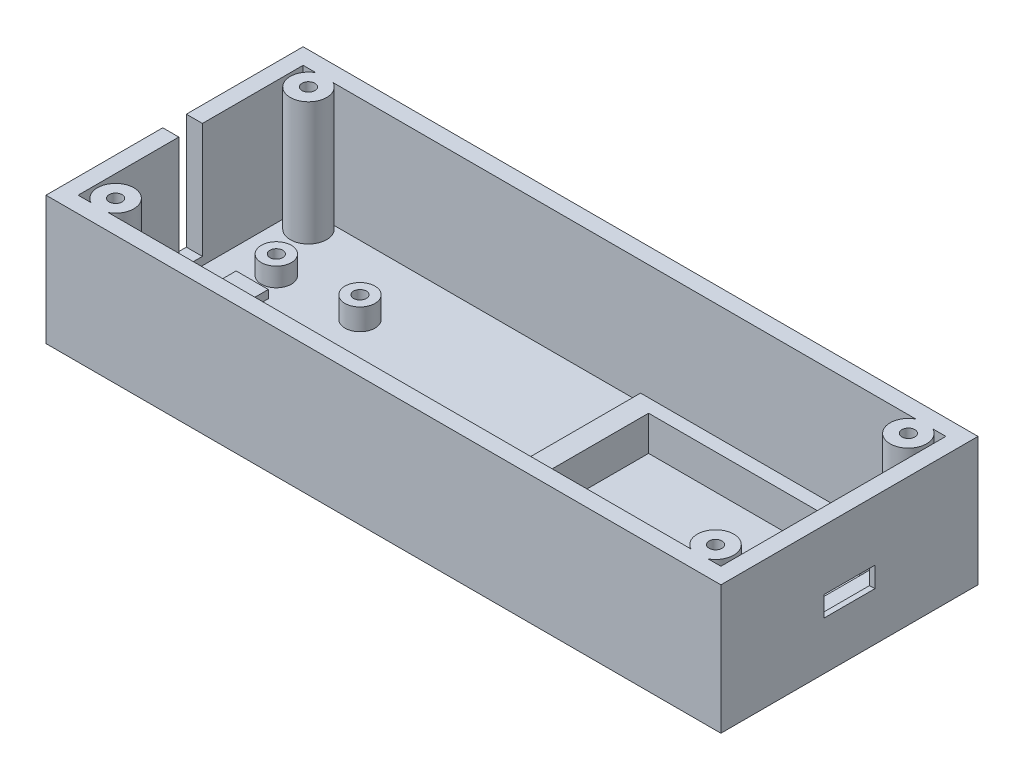
SolidWorks part; units mm, degrees
ref_plane "Front Plane" through (0, 0, 0) normal (0, 0, 1) x (1, 0, 0)
ref_plane "Top Plane" through (0, 0, 0) normal (0, 1, 0) x (1, 0, 0)
ref_plane "Right Plane" through (0, 0, 0) normal (1, 0, 0) x (0, 0, -1)
sketch "Sketch1" plane through (0, 0, 0) normal (0, 1, 0) x (1, 0, 0)
  line L0 (-63, 24) -> (63, 24)
  line L1 (63, 24) -> (63, -24)
  line L2 (63, -24) -> (-63, -24)
  line L3 (-63, -24) -> (-63, 24)
extrude "Boss-Extrude1" add sketch "Sketch1" along normal blind 25.5
chamfer "Chamfer1" distance 1.5 angle 45 4 edges at (0, 0, 24) (63, 0, 0) (0, 0, -24) (-63, 0, 0)
ref_plane "Plane1" through (0, 25.5, 0) normal (0, 1, 0) x (1, 0, 0)
sketch "Sketch2" plane through (0, 25.5, 0) normal (0, 1, 0) x (1, 0, 0)
  line L0 (-60, 21) -> (60, 21)
  line L1 (60, 21) -> (60, -21)
  line L2 (60, -21) -> (-60, -21)
  line L3 (-60, -21) -> (-60, 21)
extrude "Cut-Extrude1" cut sketch "Sketch2" against normal blind 23
sketch "Sketch3" plane through (0, 0, 0) normal (0, 1, 0) x (1, 0, 0)
  circle A0 centre (-56, 18) radius 3.4
  circle A1 centre (-56, -18) radius 3.4
  circle A2 centre (56, 18) radius 3.4
  circle A3 centre (56, -18) radius 3.4
extrude "Boss-Extrude2" add sketch "Sketch3" along normal blind 25.5
sketch "Sketch4" plane through (0, 25.5, 0) normal (0, 1, 0) x (1, 0, 0)
  circle A0 centre (-56, 18) radius 1.2
  circle A1 centre (-56, -18) radius 1.2
  circle A2 centre (56, 18) radius 1.2
  circle A3 centre (56, -18) radius 1.2
extrude "Cut-Extrude2" cut sketch "Sketch4" against normal blind 13
sketch "Sketch5" plane through (0, 0, 0) normal (0, 1, 0) x (1, 0, 0)
  circle A0 centre (-36.59, 8.21) radius 2.8
  circle A1 centre (-7.59, -8.21) radius 2.8
extrude "Boss-Extrude3" add sketch "Sketch5" along normal blind 6.5
ref_plane "Plane2" through (0, 6.5, 0) normal (0, 1, 0) x (1, 0, 0)
sketch "Sketch6" plane through (0, 6.5, 0) normal (0, 1, 0) x (1, 0, 0)
  circle A0 centre (-36.59, 8.21) radius 1.2
  circle A1 centre (-7.59, -8.21) radius 1.2
extrude "Cut-Extrude3" cut sketch "Sketch6" against normal blind 5
sketch "Sketch7" plane through (0, 0, 0) normal (0, 1, 0) x (1, 0, 0)
  circle A0 centre (-51.5, 7.5) radius 2.8
  circle A1 centre (-51.5, -7.5) radius 2.8
extrude "Boss-Extrude4" add sketch "Sketch7" along normal blind 6
sketch "Sketch8" plane through (0, 0, 0) normal (0, 1, 0) x (1, 0, 0)
  line L0 (-54.5, 3) -> (-48.5, 3)
  line L1 (-48.5, 3) -> (-48.5, -3)
  line L2 (-48.5, -3) -> (-54.5, -3)
  line L3 (-54.5, -3) -> (-54.5, 3)
extrude "Boss-Extrude5" add sketch "Sketch8" along normal blind 4
ref_plane "Plane3" through (0, 6, 0) normal (0, 1, 0) x (1, 0, 0)
sketch "Sketch9" plane through (0, 6, 0) normal (0, 1, 0) x (1, 0, 0)
  circle A0 centre (-51.5, 7.5) radius 1.2
  circle A1 centre (-51.5, -7.5) radius 1.2
extrude "Cut-Extrude4" cut sketch "Sketch9" against normal blind 5
sketch "Sketch10" plane through (0, 25.5, 0) normal (0, 1, 0) x (1, 0, 0)
  line L0 (-64, 2.2) -> (-59, 2.2)
  line L1 (-59, 2.2) -> (-59, -2.2)
  line L2 (-59, -2.2) -> (-64, -2.2)
  line L3 (-64, -2.2) -> (-64, 2.2)
extrude "Cut-Extrude5" cut sketch "Sketch10" against normal blind 21.5
sketch "Sketch11" plane through (0, 0, 0) normal (0, 1, 0) x (1, 0, 0)
  line L0 (8, 16) -> (60, 16)
  line L1 (60, 16) -> (60, -16)
  line L2 (60, -16) -> (8, -16)
  line L3 (8, -16) -> (8, 16)
  line L4 (12, 13.5) -> (58, 13.5)
  line L5 (58, 13.5) -> (58, -13.5)
  line L6 (58, -13.5) -> (12, -13.5)
  line L7 (12, -13.5) -> (12, 13.5)
extrude "Boss-Extrude6" add sketch "Sketch11" along normal blind 9
ref_plane "Plane4" through (60, 0, 0) normal (1, 0, 0) x (0, 0, -1)
sketch "Sketch12" plane through (60, 0, 0) normal (1, 0, 0) x (0, 0, -1)
  line L0 (-14.2, 9) -> (14.2, 9)
  line L1 (14.2, 9) -> (14.2, 16)
  line L2 (14.2, 16) -> (-14.2, 16)
  line L3 (-14.2, 16) -> (-14.2, 9)
extrude "Cut-Extrude7" cut sketch "Sketch12" along normal blind 2
ref_plane "Plane5" through (63, 0, 0) normal (1, 0, 0) x (0, 0, -1)
sketch "Sketch13" plane through (63, 0, 0) normal (1, 0, 0) x (0, 0, -1)
  line L0 (-4.75, 10.5) -> (4.75, 10.5)
  line L1 (4.75, 10.5) -> (4.75, 14.3)
  line L2 (4.75, 14.3) -> (-4.75, 14.3)
  line L3 (-4.75, 14.3) -> (-4.75, 10.5)
extrude "Cut-Extrude8" cut sketch "Sketch13" against normal blind 2
